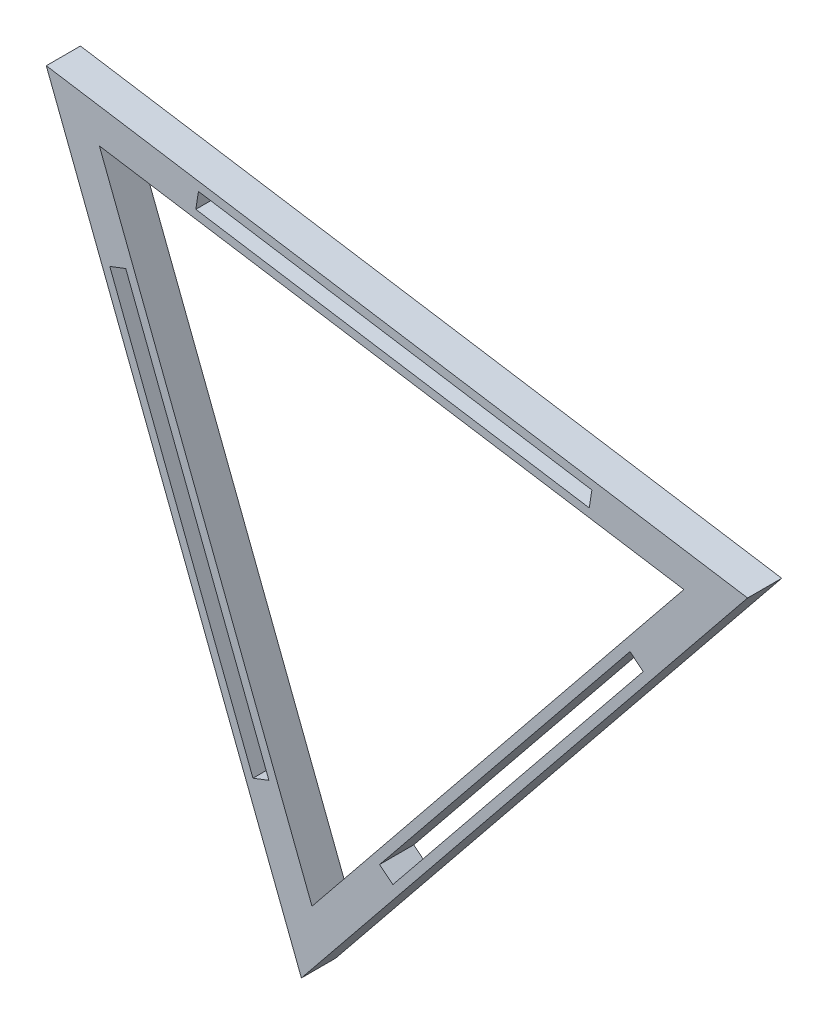
SolidWorks part; units mm, degrees
ref_plane "Plan de face" through (0, 0, 0) normal (0, 0, 1) x (1, 0, 0)
ref_plane "Plan de dessus" through (0, 0, 0) normal (0, 1, 0) x (1, 0, 0)
ref_plane "Plan de droite" through (0, 0, 0) normal (1, 0, 0) x (0, 0, -1)
sketch "Esquisse1" plane through (0, 0, 0) normal (0, 0, 1) x (1, 0, 0)
  line L0 (28.6145, 31.0095) -> (-36.7494, -49.8828)
  line L1 (-36.7494, -49.8828) -> (-74.1222, 47.1701)
  line L2 (-74.1222, 47.1701) -> (28.6145, 31.0095)
  line L3 (-83.456, 54.7121) -> (39.8129, 35.3217)
  line L4 (39.8129, 35.3217) -> (-38.6141, -61.7371)
  line L5 (-38.6141, -61.7371) -> (-83.456, 54.7121)
  dimension "D1" = 60
  dimension "D2" = 300
  dimension "D3" = 6
  dimension "D4" = 104
  dimension "D5" = 104
extrude "Boss.-Extru.2" add sketch "Esquisse1" along normal blind 6
sketch "Esquisse2" plane through (0, 0, 6) normal (0, 0, 1) x (1, 0, 0)
  line L0 (-24.8721, -37.5983) -> (19.1426, 16.8325)
  line L1 (-24.8721, -37.5983) -> (-22.5393, -39.4846)
  line L2 (39.8129, 35.3217) -> (-83.456, 54.7121) construction
  line L3 (34.2137, 33.1656) -> (-78.7891, 50.9411)
  line L4 (-78.7891, 50.9411) -> (-37.6817, -55.81)
  line L5 (-37.6817, -55.81) -> (34.2137, 33.1656)
  line L6 (28.6145, 31.0095) -> (-74.1222, 47.1701) construction
  line L7 (-36.7494, -49.8828) -> (28.6145, 31.0095) construction
  line L8 (-74.1222, 47.1701) -> (-36.7494, -49.8828) construction
  line L9 (19.1426, 16.8325) -> (21.4754, 14.9461)
  line L10 (-22.5393, -39.4846) -> (21.4754, 14.9461)
  line L11 (-24.8721, -37.5983) -> (21.4754, 14.9461) construction
  line L12 (19.1426, 16.8325) -> (-22.5393, -39.4846) construction
  line L13 (-57.1726, 45.991) -> (11.9779, 35.1184)
  line L14 (-57.1726, 45.991) -> (-56.7066, 48.9546)
  line L15 (11.9779, 35.1184) -> (12.4439, 38.082)
  line L16 (-56.7066, 48.9546) -> (12.4439, 38.082)
  line L17 (-57.1726, 45.991) -> (12.4439, 38.082) construction
  line L18 (11.9779, 35.1184) -> (-56.7066, 48.9546) construction
  line L19 (-47.1279, -35.5783) -> (-72.2891, 29.7433)
  line L20 (-47.1279, -35.5783) -> (-44.3284, -34.5)
  line L21 (-72.2891, 29.7433) -> (-69.4896, 30.8216)
  line L22 (-44.3284, -34.5) -> (-69.4896, 30.8216)
  line L23 (-47.1279, -35.5783) -> (-69.4896, 30.8216) construction
  line L24 (-72.2891, 29.7433) -> (-44.3284, -34.5) construction
  circle A0 centre (-27.419, 9.4322) radius 33.0222 construction
  point P1 (-1.6983, -11.3261)
  point P2 (-22.3643, 42.0365)
  point P3 (-58.3087, -2.3783)
  dimension "D1" = 3
  dimension "D2" = 3
  dimension "D3" = 3
  dimension "D4" = 3
  dimension "D5" = 3
  dimension "D6" = 3
  dimension "D7" = 70
  dimension "D8" = 70
  dimension "D9" = 70
extrude "Enlèv. mat.-Extru.2" cut sketch "Esquisse2" against normal blind 10 contours L9 L10 L1 L0 | L14 L16 L15 L13 | L20 L22 L21 L19
